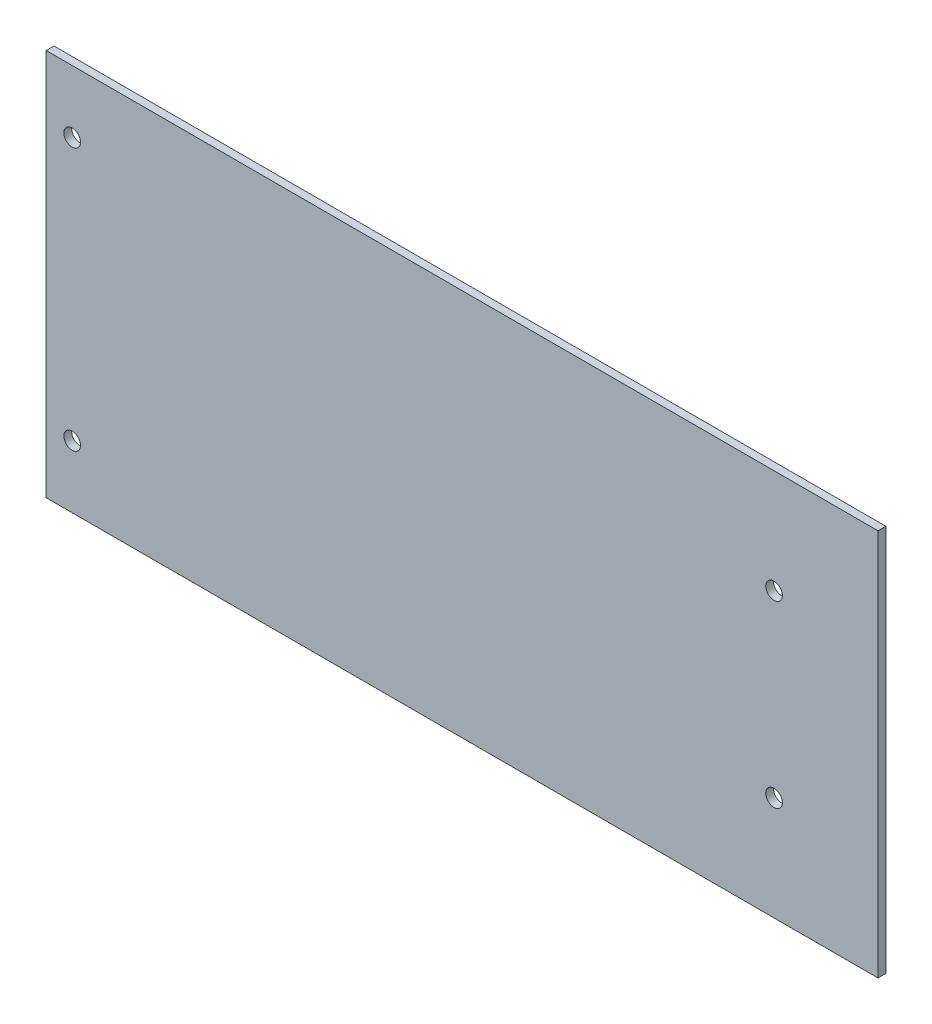
SolidWorks part; units mm, degrees
ref_plane "Front Plane" through (0, 0, 0) normal (0, 0, 1) x (1, 0, 0)
ref_plane "Top Plane" through (0, 0, 0) normal (0, 1, 0) x (1, 0, 0)
ref_plane "Right Plane" through (0, 0, 0) normal (1, 0, 0) x (0, 0, -1)
sketch "Sketch1" plane through (0, 0, 0) normal (0, 0, 1) x (1, 0, 0)
  line L0 (70.0372, 83.5868) -> (70.0372, -13.3929) construction
  line L1 (-69.9628, 74.5) -> (90.0372, 74.5)
  line L2 (-69.9628, 74.5) -> (-69.9628, 0)
  line L3 (-69.9628, 0) -> (90.0372, 0)
  line L4 (90.0372, 74.5) -> (90.0372, 0)
  line L5 (55.0184, 54.5) -> (110.3139, 54.5) construction
  line L6 (59.0592, 20) -> (101.5942, 20) construction
  line L7 (-64.9628, 79.5864) -> (-64.9628, -13.3929) construction
  line L8 (-59.8881, 62.5) -> (-80.3167, 62.5) construction
  line L9 (-55.3983, 12) -> (-78.7452, 12) construction
  circle A0 centre (70.0372, 54.5) radius 1.6
  circle A1 centre (70.0372, 20) radius 1.6
  circle A2 centre (-64.9628, 62.5) radius 1.6
  circle A3 centre (-64.9628, 12) radius 1.6
  dimension "D6" = 5
  dimension "D1" = 74.5
  dimension "D2" = 160
  dimension "D3" = 20
  dimension "D4" = 20
  dimension "D5" = 20
  dimension "D7" = 12
  dimension "D8" = 12
extrude "Boss-Extrude1" add sketch "Sketch1" along normal blind 1.5
